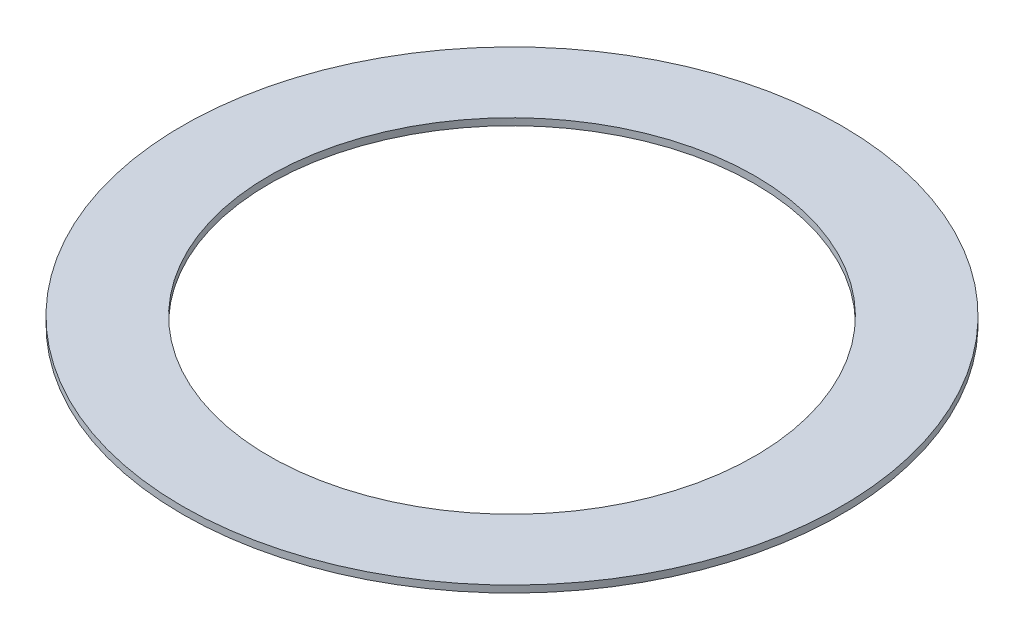
SolidWorks part; units mm, degrees
ref_plane "Ebene vorne" through (0, 0, 0) normal (0, 0, 1) x (1, 0, 0)
ref_plane "Ebene oben" through (0, 0, 0) normal (0, 1, 0) x (1, 0, 0)
ref_plane "Ebene rechts" through (0, 0, 0) normal (1, 0, 0) x (0, 0, -1)
sketch "Skizze1" plane through (0, 0, 0) normal (0, 0, 1) x (1, 0, 0)
  line L0 (0, 0) -> (0, 47.8538) construction
  line L1 (35, 0) -> (47.5, 0)
  line L2 (47.5, 0) -> (47.5, 1)
  line L3 (47.5, 1) -> (35, 1)
  line L4 (35, 1) -> (35, 0)
  point P5 (35, 0.1039)
  dimension "D1" = 70
  dimension "D2" = 95
  dimension "D3" = 1
revolve "Rotation1" add sketch "Skizze1" angle 360 about L0
